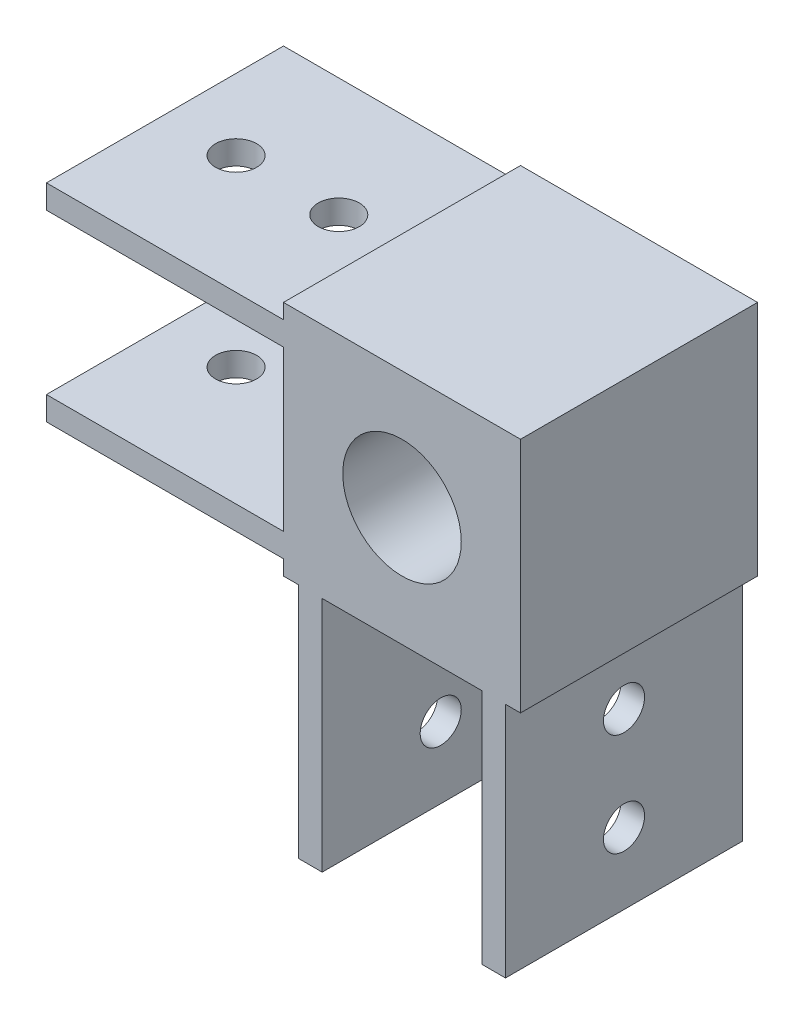
SolidWorks part; units mm, degrees
ref_plane "前视基准面" through (0, 0, 0) normal (0, 0, 1) x (1, 0, 0)
ref_plane "上视基准面" through (0, 0, 0) normal (0, 1, 0) x (1, 0, 0)
ref_plane "右视基准面" through (0, 0, 0) normal (1, 0, 0) x (0, 0, -1)
other "Configuration Table"
sketch "草图1" plane through (0, 0, 0) normal (0, 0, 1) x (1, 0, 0)
  line L0 (0, -15) -> (0, -48.3156) construction
  line L1 (-15, -15) -> (-13.1, -15)
  line L2 (-15, -15) -> (-15, -13.1)
  line L3 (-15, 15) -> (15, 15)
  line L4 (15, -15) -> (15, 15)
  line L5 (-15, -15) -> (15, 15) construction
  line L6 (-15, 15) -> (15, -15) construction
  line L8 (-13.1, -15) -> (-13.1, -45)
  line L9 (-13.1, -45) -> (-10.1, -45)
  line L10 (-10.1, -15) -> (-10.1, -45)
  line L12 (10.1, -15) -> (10.1, -45)
  line L13 (10.1, -45) -> (13.1, -45)
  line L14 (13.1, -15) -> (13.1, -45)
  line L15 (-10.1, -15) -> (10.1, -15)
  line L16 (13.1, -15) -> (15, -15)
  line L17 (-15, 0) -> (-50.6235, 0) construction
  line L18 (-15, 13.1) -> (-45, 13.1)
  line L20 (-15, 10.1) -> (-45, 10.1)
  line L21 (-45, 13.1) -> (-45, 10.1)
  line L22 (-15, -13.1) -> (-45, -13.1)
  line L24 (-15, -10.1) -> (-45, -10.1)
  line L25 (-45, -13.1) -> (-45, -10.1)
  line L26 (-15, 13.1) -> (-15, 15)
  line L27 (-15, -10.1) -> (-15, 10.1)
  point P0 (0, 0)
  dimension "D1" = 30
  dimension "D2" = 30
  dimension "D3" = 3
  dimension "D4" = 20.2
  dimension "D5" = 30
  dimension "D6" = 3
  dimension "D7" = 20.2
  dimension "D8" = 30
extrude "凸台-拉伸1" add sketch "草图1" along normal blind 30
sketch "草图2" plane through (0, 0, 30) normal (0, 0, 1) x (1, 0, 0)
  circle A0 centre (0, 0) radius 7.5
  dimension "D1" = 15
extrude "切除-拉伸1" cut sketch "草图2" against normal through all
sketch "草图5" plane through (13.1, 0, 0) normal (1, 0, 0) x (0, 0, -1)
  line L0 (-30, -45) -> (-30, -15) construction
  line L3 (-30, -15) -> (0, -15) construction
  line L4 (-30, -45) -> (0, -45) construction
  circle A0 centre (-15, -23) radius 2.6
  circle A1 centre (-15, -36) radius 2.6
  point P4 (0, 0)
  point P9 (-15.621, -15)
  dimension "D1" = 5.2
  dimension "D2" = 15
  dimension "D3" = 8
  dimension "D4" = 9
extrude "切除-拉伸4" cut sketch "草图5" against normal through all
sketch "草图6" plane through (0, 13.1, 0) normal (0, 1, 0) x (1, 0, 0)
  line L0 (-15, -30) -> (-45, -30) construction
  line L1 (-15, -30) -> (-15, 0) construction
  line L2 (-45, -30) -> (-45, 0) construction
  circle A0 centre (-23, -15) radius 2.6
  circle A1 centre (-36, -15) radius 2.6
  point P4 (0, 0)
  dimension "D1" = 5.2
  dimension "D2" = 15
  dimension "D3" = 8
  dimension "D4" = 9
extrude "切除-拉伸5" cut sketch "草图6" against normal through all
